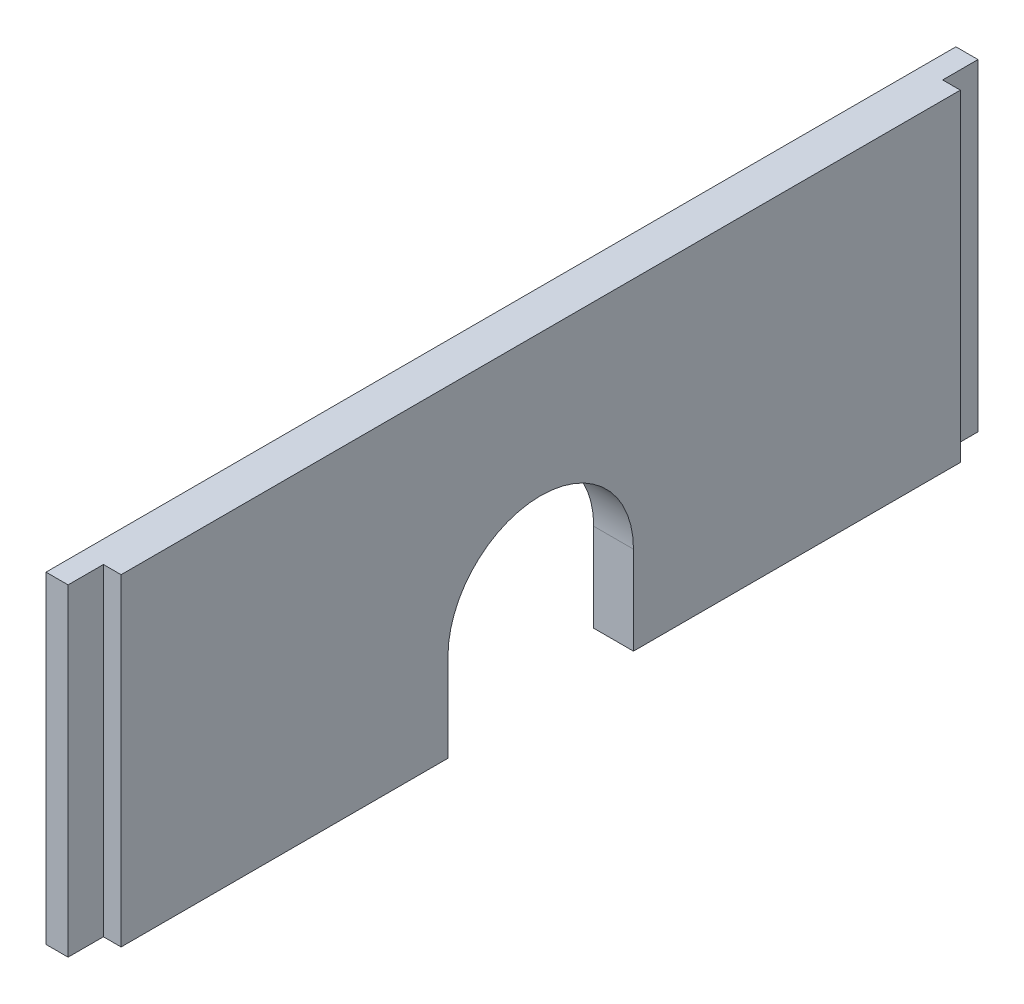
SolidWorks part; units mm, degrees
ref_plane "정면" through (0, 0, 0) normal (0, 0, 1) x (1, 0, 0)
ref_plane "윗면" through (0, 0, 0) normal (0, 1, 0) x (1, 0, 0)
ref_plane "우측면" through (0, 0, 0) normal (1, 0, 0) x (0, 0, -1)
sketch "스케치1" plane through (0, 0, 0) normal (0, 1, 0) x (1, 0, 0)
  line L1 (0, 0) -> (2.5, 0)
  line L2 (0, 0) -> (0, -103)
  line L3 (0, -103) -> (2.5, -103)
  line L4 (2.5, 0) -> (2.5, -103)
  line L5 (2.5, -4) -> (4.5, -4)
  line L6 (2.5, -4) -> (2.5, -99)
  line L7 (2.5, -99) -> (4.5, -99)
  line L8 (4.5, -4) -> (4.5, -99)
  dimension "D1" = 103
  dimension "D2" = 2.5
  dimension "D3" = 95
  dimension "D4" = 4
extrude "보스-돌출1" add sketch "스케치1" along normal blind 99.5 contours L4 L1 L2 L3 | L8 L5 L4 L7
sketch "스케치2" plane through (4.5, 0, 0) normal (1, 0, 0) x (0, 0, -1)
  line L0 (-4, 0) -> (-99, 0) construction
  line L1 (-51.5, 0) -> (-51.5, 17.427) construction
  line L2 (-62, 10) -> (-62, 0)
  line L3 (-41, 10) -> (-41, 0)
  line L4 (-62, 0) -> (-41, 0)
  arc A0 (-41, 10) -> (-62, 10) centre (-51.5, 10) ccw
  dimension "D1" = 21
  dimension "D2" = 10
extrude "컷-돌출2" cut sketch "스케치2" against normal up to surface (4.5 mm away) up to face at (0, 49.75, 51.5)
sketch "스케치3" plane through (0, 99.5, 0) normal (0, 1, 0) x (1, 0, 0)
  line L8 (2.5, -4) -> (2.5, 0)
  line L9 (2.5, 0) -> (0, 0)
  line L10 (0, 0) -> (0, -103)
  line L11 (0, -103) -> (2.5, -103)
  line L12 (2.5, -103) -> (2.5, -99)
  line L13 (2.5, -99) -> (4.5, -99)
  line L14 (4.5, -99) -> (4.5, -4)
  line L15 (4.5, -4) -> (2.5, -4)
  line L16 (2.5, -4) -> (2.5, 0)
  line L17 (2.5, 0) -> (0, 0)
  line L18 (0, 0) -> (0, -103)
  line L19 (0, -103) -> (2.5, -103)
  line L20 (2.5, -103) -> (2.5, -99)
  line L21 (2.5, -99) -> (4.5, -99)
  line L22 (4.5, -99) -> (4.5, -4)
  line L23 (4.5, -4) -> (2.5, -4)
  dimension "D1" = 0
extrude "컷-돌출3" cut sketch "스케치3" against normal blind 58.5
sketch "스케치4" plane through (0, 41, 0) normal (0, 1, 0) x (1, 0, 0)
  line L8 (4.5, -4) -> (2.5, -4)
  line L9 (2.5, -4) -> (2.5, 0)
  line L10 (2.5, 0) -> (0, 0)
  line L11 (0, 0) -> (0, -103)
  line L12 (0, -103) -> (2.5, -103)
  line L13 (2.5, -103) -> (2.5, -99)
  line L14 (2.5, -99) -> (4.5, -99)
  line L15 (4.5, -99) -> (4.5, -4)
  line L16 (4.5, -4) -> (2.5, -4)
  line L17 (2.5, -4) -> (2.5, 0)
  line L18 (2.5, 0) -> (0, 0)
  line L19 (0, 0) -> (0, -103)
  line L20 (0, -103) -> (2.5, -103)
  line L21 (2.5, -103) -> (2.5, -99)
  line L22 (2.5, -99) -> (4.5, -99)
  line L23 (4.5, -99) -> (4.5, -4)
  dimension "D1" = 0
extrude "컷-돌출4" cut sketch "스케치4" against normal blind 4.5
sketch "스케치5" plane through (0, 36.5, 0) normal (0, 1, 0) x (1, 0, 0)
  line L8 (4.5, -99) -> (4.5, -4)
  line L9 (4.5, -4) -> (2.5, -4)
  line L10 (2.5, -4) -> (2.5, 0)
  line L11 (2.5, 0) -> (0, 0)
  line L12 (0, 0) -> (0, -103)
  line L13 (0, -103) -> (2.5, -103)
  line L14 (2.5, -103) -> (2.5, -99)
  line L15 (2.5, -99) -> (4.5, -99)
  line L16 (4.5, -99) -> (4.5, -4)
  line L17 (4.5, -4) -> (2.5, -4)
  line L18 (2.5, -4) -> (2.5, 0)
  line L19 (2.5, 0) -> (0, 0)
  line L20 (0, 0) -> (0, -103)
  line L21 (0, -103) -> (2.5, -103)
  line L22 (2.5, -103) -> (2.5, -99)
  line L23 (2.5, -99) -> (4.5, -99)
  dimension "D1" = 0
sketch "스케치6" plane through (0, 0, 0) normal (0, -1, 0) x (1, 0, 0)
  line L0 (0, 62) -> (0, 103) construction
  line L1 (0, 82.5) -> (1.6, 82.5)
  line L2 (0, 82.5) -> (0, 65.5)
  line L3 (0, 65.5) -> (1.6, 65.5)
  line L4 (1.6, 82.5) -> (1.6, 65.5)
extrude "컷-돌출5" cut sketch "스케치6" against normal blind 10
